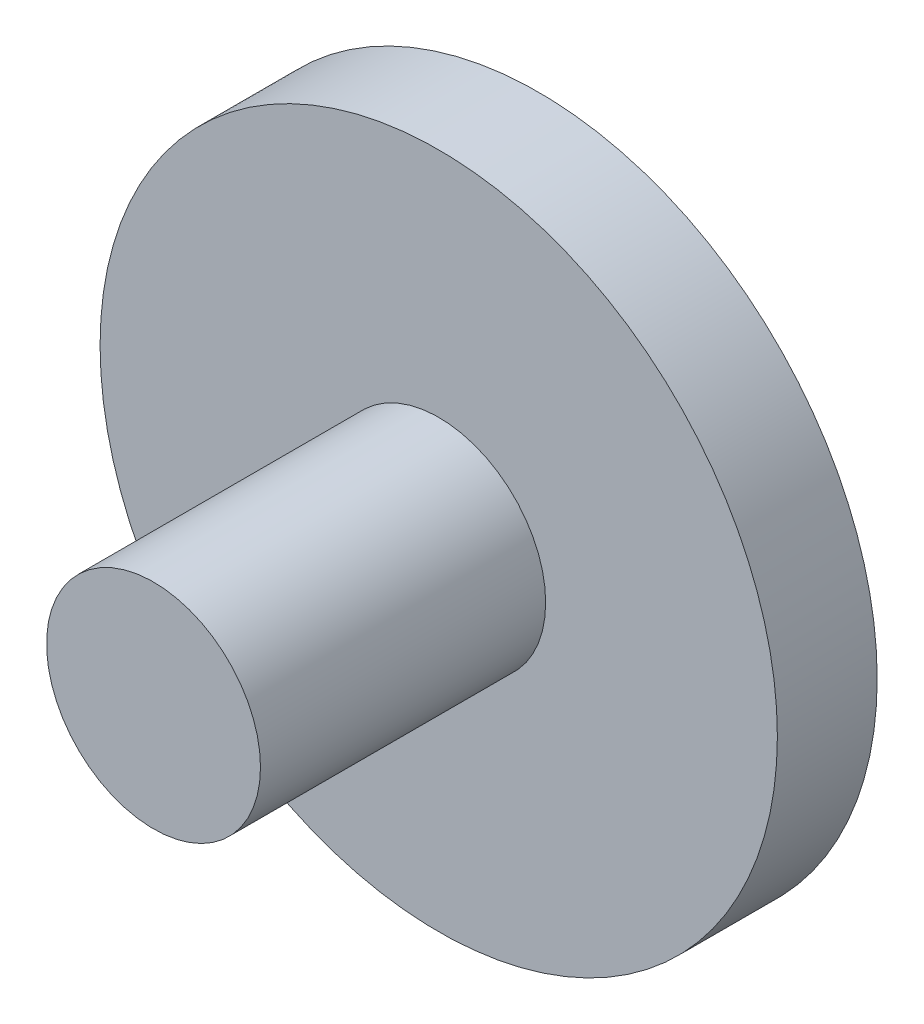
SolidWorks part; units mm, degrees
material "AISI 304"
ref_plane "前视基准面" through (0, 0, 0) normal (0, 0, 1) x (1, 0, 0)
ref_plane "上视基准面" through (0, 0, 0) normal (0, 1, 0) x (1, 0, 0)
ref_plane "右视基准面" through (0, 0, 0) normal (1, 0, 0) x (0, 0, -1)
sketch "草图1" plane through (0, 0, 0) normal (0, 0, 1) x (1, 0, 0)
  circle A0 centre (0, 0) radius 4.75
  dimension "D1" = 9.5
extrude "凸台-拉伸1" add sketch "草图1" along normal blind 1.4
sketch "草图2" plane through (0, 0, 1.4) normal (0, 0, 1) x (1, 0, 0)
  circle A0 centre (0, 0) radius 1.5
  dimension "D1" = 3
extrude "凸台-拉伸2" add sketch "草图2" along normal blind 4
cosmetic thread "装饰螺纹线1" parameters "D2"=2
sketch "草图3" plane through (0, 0, 0) normal (0, 0, -1) x (-1, 0, 0)
  line L1 (-0.3802, -2.5839) -> (0.3802, -2.5839)
  line L2 (-0.3802, -2.5839) -> (-0.3802, 2.5839)
  line L3 (-0.3802, 2.5839) -> (0.3802, 2.5839)
  line L4 (0.3802, -2.5839) -> (0.3802, 2.5839)
  line L5 (-0.3802, -2.5839) -> (0.3802, 2.5839) construction
  line L6 (-0.3802, 2.5839) -> (0.3802, -2.5839) construction
  line L7 (-1.516, -0.3123) -> (1.516, -0.3123)
  line L8 (-1.516, -0.3123) -> (-1.516, 0.3123)
  line L9 (-1.516, 0.3123) -> (1.516, 0.3123)
  line L10 (1.516, -0.3123) -> (1.516, 0.3123)
  line L11 (-1.516, -0.3123) -> (1.516, 0.3123) construction
  line L12 (-1.516, 0.3123) -> (1.516, -0.3123) construction
  point P0 (0, 0)
  point P6 (0, 0)
extrude "切除-拉伸1" cut sketch "草图3" against normal blind 1 contours L2 L9 L4 L3 | L9 L8 L7 L2 | L7 L10 L9 L4 | L7 L2 L1 L4 | L9 L2 L7 L4
